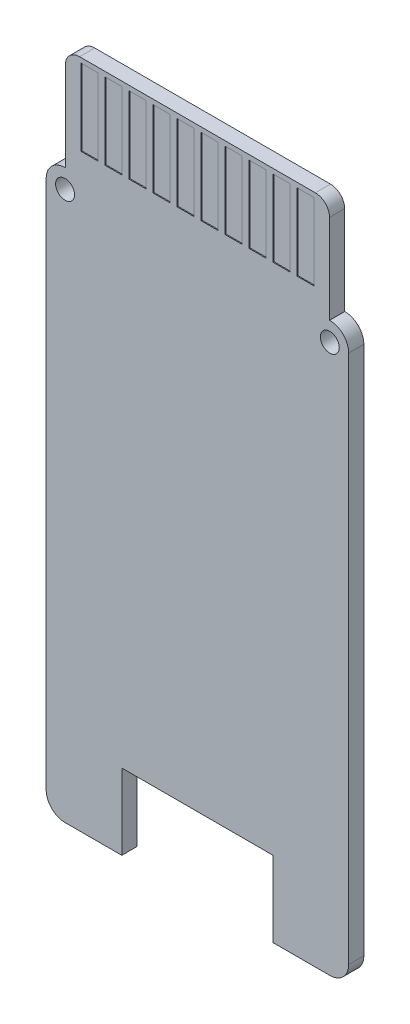
SolidWorks part; units mm, degrees
ref_plane "前视基准面" through (0, 0, 0) normal (0, 0, 1) x (1, 0, 0)
ref_plane "上视基准面" through (0, 0, 0) normal (0, 1, 0) x (1, 0, 0)
ref_plane "右视基准面" through (0, 0, 0) normal (1, 0, 0) x (0, 0, -1)
other "Configuration Table"
sketch "草图1" plane through (0, 0, 0) normal (0, 0, 1) x (1, 0, 0)
  line L1 (-14, 30) -> (14, 30)
  line L2 (-16, 28) -> (-16, -28)
  line L3 (-14, -30) -> (14, -30)
  line L4 (16, 28) -> (16, -28)
  arc A0 (-16, -28) -> (-14, -30) centre (-14, -28) ccw
  arc A1 (14, -30) -> (16, -28) centre (14, -28) ccw
  arc A2 (-14, 30) -> (-16, 28) centre (-14, 28) ccw
  arc A3 (16, 28) -> (14, 30) centre (14, 28) ccw
  circle A4 centre (-14, 28) radius 1
  circle A5 centre (14, 28) radius 1
  point P0 (0, 0)
  dimension "D3" = 4
  dimension "D4" = 4
  dimension "D5" = 4
  dimension "D6" = 4
  dimension "D7" = 2
  dimension "D8" = 2
  dimension "D2" = 14
  dimension "D9" = 32
  dimension "D10" = 60
  dimension "D11" = 30
extrude "凸台-拉伸1" add sketch "草图1" along normal blind 1.6
sketch "草图2" plane through (0, 0, 0) normal (0, 0, 1) x (1, 0, 0)
  line L0 (-14, -30) -> (14, -30) construction
  line L1 (-8, -30) -> (8, -30)
  line L2 (-8, -30) -> (-8, -22)
  line L3 (-8, -22) -> (8, -22)
  line L4 (8, -30) -> (8, -22)
  line L5 (16, -28) -> (16, 28) construction
  line L6 (-16, 28) -> (-16, -28) construction
  dimension "D1" = 8
  dimension "D2" = 8
  dimension "D3" = 8
extrude "切除-拉伸1" cut sketch "草图2" along normal blind 1.6
sketch "草图3" plane through (0, 0, 0) normal (0, 0, 1) x (1, 0, 0)
  line L0 (14, 30) -> (-14, 30) construction
  line L1 (-13.97, 30) -> (13.97, 30)
  line L2 (-13.97, 30) -> (-13.97, 40.92) construction
  line L3 (-13.97, 40.92) -> (13.97, 40.92) construction
  line L4 (13.97, 30) -> (13.97, 40.92) construction
  line L5 (-13.97, 39.42) -> (-13.97, 30)
  line L6 (-12.47, 40.92) -> (12.47, 40.92)
  line L7 (13.97, 39.42) -> (13.97, 30)
  arc A0 (-12.47, 40.92) -> (-13.97, 39.42) centre (-12.47, 39.42) ccw
  arc A1 (13.97, 39.42) -> (12.47, 40.92) centre (12.47, 39.42) ccw
  point P6 (0, 30)
  point P7 (0, 40.92)
  dimension "D3" = 3
  dimension "D4" = 3
  dimension "D1" = 27.94
  dimension "D2" = 10.92
extrude "凸台-拉伸2" add sketch "草图3" along normal blind 1.6
sketch "草图4" plane through (0, 0, 0) normal (0, 0, 1) x (1, 0, 0)
  line L0 (0, -1000) -> (0, 49000) construction
  line L1 (-2.16, 40.42) -> (-0.38, 40.42)
  line L2 (-2.16, 40.42) -> (-2.16, 32.32)
  line L3 (-2.16, 32.32) -> (-0.38, 32.32)
  line L4 (-0.38, 40.42) -> (-0.38, 32.32)
  line L5 (12.47, 40.92) -> (-12.47, 40.92) construction
  line L6 (-4.7, 40.42) -> (-2.92, 40.42)
  line L7 (-4.7, 40.42) -> (-4.7, 32.32)
  line L8 (-4.7, 32.32) -> (-2.92, 32.32)
  line L9 (-2.92, 40.42) -> (-2.92, 32.32)
  line L10 (-7.24, 40.42) -> (-5.46, 40.42)
  line L11 (-7.24, 40.42) -> (-7.24, 32.32)
  line L12 (-7.24, 32.32) -> (-5.46, 32.32)
  line L13 (-5.46, 40.42) -> (-5.46, 32.32)
  line L14 (-9.78, 40.42) -> (-8, 40.42)
  line L15 (-9.78, 40.42) -> (-9.78, 32.32)
  line L16 (-9.78, 32.32) -> (-8, 32.32)
  line L17 (-8, 40.42) -> (-8, 32.32)
  line L18 (-12.32, 40.42) -> (-10.54, 40.42)
  line L19 (-12.32, 40.42) -> (-12.32, 32.32)
  line L20 (-12.32, 32.32) -> (-10.54, 32.32)
  line L21 (-10.54, 40.42) -> (-10.54, 32.32)
  line L22 (-2.16, 40.42) -> (-4.7, 40.42) construction
  line L23 (2.16, 40.42) -> (4.7, 40.42) construction
  line L24 (10.54, 40.42) -> (10.54, 32.32)
  line L25 (12.32, 32.32) -> (10.54, 32.32)
  line L26 (12.32, 40.42) -> (12.32, 32.32)
  line L27 (12.32, 40.42) -> (10.54, 40.42)
  line L28 (8, 40.42) -> (8, 32.32)
  line L29 (9.78, 32.32) -> (8, 32.32)
  line L30 (9.78, 40.42) -> (9.78, 32.32)
  line L31 (9.78, 40.42) -> (8, 40.42)
  line L32 (5.46, 40.42) -> (5.46, 32.32)
  line L33 (7.24, 32.32) -> (5.46, 32.32)
  line L34 (7.24, 40.42) -> (7.24, 32.32)
  line L35 (7.24, 40.42) -> (5.46, 40.42)
  line L36 (2.92, 40.42) -> (2.92, 32.32)
  line L37 (4.7, 32.32) -> (2.92, 32.32)
  line L38 (4.7, 40.42) -> (4.7, 32.32)
  line L39 (4.7, 40.42) -> (2.92, 40.42)
  line L40 (0.38, 40.42) -> (0.38, 32.32)
  line L41 (2.16, 32.32) -> (0.38, 32.32)
  line L42 (2.16, 40.42) -> (2.16, 32.32)
  line L43 (2.16, 40.42) -> (0.38, 40.42)
  dimension "D1" = 1.78
  dimension "D2" = 8.1
  dimension "D3" = 0.38
  dimension "D4" = 0.5
  dimension "D6" = 2.54
  dimension "D5" = 5
extrude "切除-拉伸2" cut sketch "草图4" along normal blind 0.1
sketch "草图5" plane through (0, 0, 0) normal (0, 0, 1) x (1, 0, 0)
  line L4 (-2.92, 40.42) -> (-4.7, 40.42)
  line L5 (-2.92, 32.32) -> (-2.92, 40.42)
  line L6 (-4.7, 32.32) -> (-2.92, 32.32)
  line L7 (-4.7, 40.42) -> (-4.7, 32.32)
  line L8 (-2.92, 40.42) -> (-4.7, 40.42)
  line L9 (-2.92, 32.32) -> (-2.92, 40.42)
  line L10 (-4.7, 32.32) -> (-2.92, 32.32)
  line L11 (-4.7, 40.42) -> (-4.7, 32.32)
  line L12 (-0.38, 40.42) -> (-2.16, 40.42)
  line L13 (-0.38, 32.32) -> (-0.38, 40.42)
  line L14 (-2.16, 32.32) -> (-0.38, 32.32)
  line L15 (-2.16, 40.42) -> (-2.16, 32.32)
  line L16 (-0.38, 40.42) -> (-2.16, 40.42)
  line L17 (-0.38, 32.32) -> (-0.38, 40.42)
  line L18 (-2.16, 32.32) -> (-0.38, 32.32)
  line L19 (-2.16, 40.42) -> (-2.16, 32.32)
  line L20 (-10.54, 40.42) -> (-12.32, 40.42)
  line L21 (-10.54, 32.32) -> (-10.54, 40.42)
  line L22 (-12.32, 32.32) -> (-10.54, 32.32)
  line L23 (-12.32, 40.42) -> (-12.32, 32.32)
  line L24 (-10.54, 40.42) -> (-12.32, 40.42)
  line L25 (-10.54, 32.32) -> (-10.54, 40.42)
  line L26 (-12.32, 32.32) -> (-10.54, 32.32)
  line L27 (-12.32, 40.42) -> (-12.32, 32.32)
  line L28 (-8, 40.42) -> (-9.78, 40.42)
  line L29 (-8, 32.32) -> (-8, 40.42)
  line L30 (-9.78, 32.32) -> (-8, 32.32)
  line L31 (-9.78, 40.42) -> (-9.78, 32.32)
  line L32 (-8, 40.42) -> (-9.78, 40.42)
  line L33 (-8, 32.32) -> (-8, 40.42)
  line L34 (-9.78, 32.32) -> (-8, 32.32)
  line L35 (-9.78, 40.42) -> (-9.78, 32.32)
  line L36 (-5.46, 40.42) -> (-7.24, 40.42)
  line L37 (-7.24, 40.42) -> (-7.24, 32.32)
  line L38 (-7.24, 32.32) -> (-5.46, 32.32)
  line L39 (-5.46, 32.32) -> (-5.46, 40.42)
  line L40 (-5.46, 40.42) -> (-7.24, 40.42)
  line L41 (-7.24, 40.42) -> (-7.24, 32.32)
  line L42 (-7.24, 32.32) -> (-5.46, 32.32)
  line L43 (-5.46, 32.32) -> (-5.46, 40.42)
  line L44 (0.38, 40.42) -> (0.38, 32.32)
  line L45 (0.38, 32.32) -> (2.16, 32.32)
  line L46 (2.16, 32.32) -> (2.16, 40.42)
  line L47 (2.16, 40.42) -> (0.38, 40.42)
  line L48 (0.38, 40.42) -> (0.38, 32.32)
  line L49 (0.38, 32.32) -> (2.16, 32.32)
  line L50 (2.16, 32.32) -> (2.16, 40.42)
  line L51 (2.16, 40.42) -> (0.38, 40.42)
  line L52 (2.92, 40.42) -> (2.92, 32.32)
  line L53 (2.92, 32.32) -> (4.7, 32.32)
  line L54 (4.7, 32.32) -> (4.7, 40.42)
  line L55 (4.7, 40.42) -> (2.92, 40.42)
  line L56 (2.92, 40.42) -> (2.92, 32.32)
  line L57 (2.92, 32.32) -> (4.7, 32.32)
  line L58 (4.7, 32.32) -> (4.7, 40.42)
  line L59 (4.7, 40.42) -> (2.92, 40.42)
  line L60 (5.46, 40.42) -> (5.46, 32.32)
  line L61 (5.46, 32.32) -> (7.24, 32.32)
  line L62 (7.24, 32.32) -> (7.24, 40.42)
  line L63 (7.24, 40.42) -> (5.46, 40.42)
  line L64 (5.46, 40.42) -> (5.46, 32.32)
  line L65 (5.46, 32.32) -> (7.24, 32.32)
  line L66 (7.24, 32.32) -> (7.24, 40.42)
  line L67 (7.24, 40.42) -> (5.46, 40.42)
  line L68 (8, 40.42) -> (8, 32.32)
  line L69 (8, 32.32) -> (9.78, 32.32)
  line L70 (9.78, 32.32) -> (9.78, 40.42)
  line L71 (9.78, 40.42) -> (8, 40.42)
  line L72 (8, 40.42) -> (8, 32.32)
  line L73 (8, 32.32) -> (9.78, 32.32)
  line L74 (9.78, 32.32) -> (9.78, 40.42)
  line L75 (9.78, 40.42) -> (8, 40.42)
  line L76 (12.32, 32.32) -> (12.32, 40.42)
  line L77 (10.54, 32.32) -> (12.32, 32.32)
  line L78 (10.54, 40.42) -> (10.54, 32.32)
  line L79 (12.32, 40.42) -> (10.54, 40.42)
  line L80 (12.32, 32.32) -> (12.32, 40.42)
  line L81 (10.54, 32.32) -> (12.32, 32.32)
  line L82 (10.54, 40.42) -> (10.54, 32.32)
  line L83 (12.32, 40.42) -> (10.54, 40.42)
  dimension "D1" = 0
  dimension "D2" = 0
  dimension "D3" = 0
  dimension "D4" = 0
  dimension "D5" = 0
  dimension "D6" = 0
  dimension "D7" = 0
  dimension "D8" = 0
  dimension "D9" = 0
  dimension "D10" = 0
extrude "切除-拉伸3" cut sketch "草图5" against normal blind 0.1 from surface at 1.6 starting at face at (-13, 28, 1.6)
